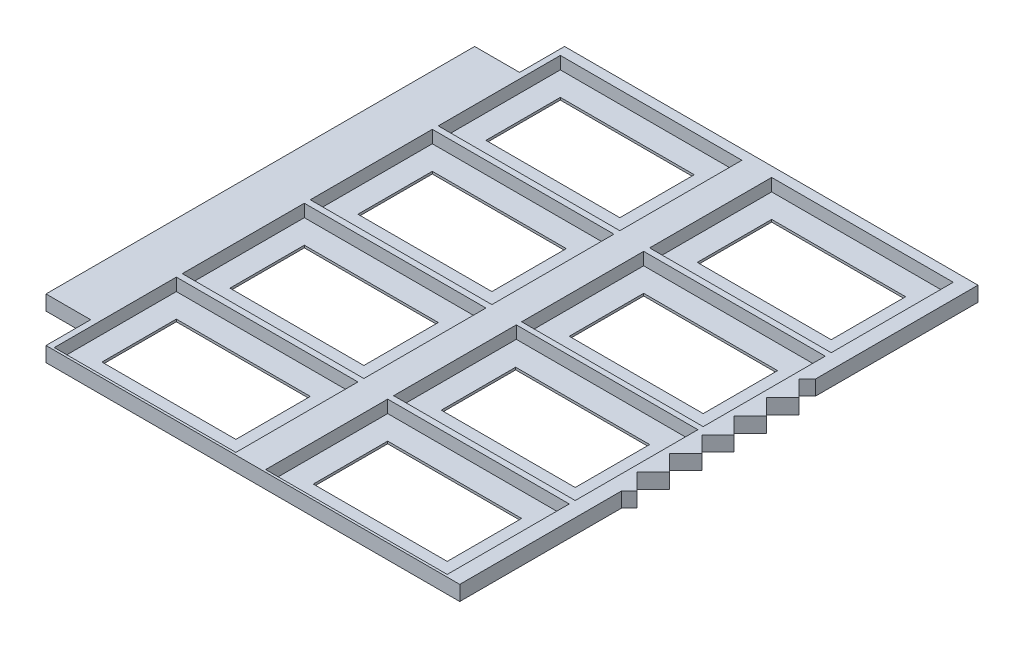
SolidWorks part; units mm, degrees
ref_plane "Front Plane" through (0, 0, 0) normal (0, 0, 1) x (1, 0, 0)
ref_plane "Top Plane" through (0, 0, 0) normal (0, 1, 0) x (1, 0, 0)
ref_plane "Right Plane" through (0, 0, 0) normal (1, 0, 0) x (0, 0, -1)
sketch "Sketch1" plane through (0, 0, 0) normal (0, 1, 0) x (1, 0, 0)
  line L0 (139.065, 94.1103) -> (139.065, -88.9) construction
  line L1 (-148.59, -107.95) -> (148.59, -107.95)
  line L2 (148.59, -107.95) -> (123.19, -107.95)
  line L3 (-156.21, 113.1603) -> (-137.0297, 113.1603)
  line L4 (148.59, -107.95) -> (148.59, 107.95)
  line L7 (148.59, -107.95) -> (-156.21, -107.95)
  line L8 (148.59, -107.95) -> (148.59, 113.1603)
  line L9 (148.59, 113.1603) -> (-156.21, 113.1603)
  line L10 (-156.21, -107.95) -> (-156.21, 113.1603)
  line L11 (-156.21, -107.95) -> (148.59, -107.95)
  line L12 (-156.21, -107.95) -> (-156.21, -106.95)
  line L13 (-156.21, -106.95) -> (148.59, -106.95)
  line L14 (148.59, -107.95) -> (148.59, -106.95)
  line L15 (148.59, -107.95) -> (148.59, 113.1603)
  line L16 (148.59, 113.1603) -> (123.19, 113.1603)
  line L17 (123.19, -107.95) -> (123.19, 113.1603)
  line L18 (123.19, -106.95) -> (45.72, -106.95)
  line L19 (123.19, -106.95) -> (123.19, -54.88)
  line L20 (123.19, -54.88) -> (45.72, -54.88)
  line L21 (45.72, -106.95) -> (45.72, -54.88)
  line L22 (123.19, -52.34) -> (45.72, -52.34)
  line L23 (123.19, -52.34) -> (123.19, -0.27)
  line L24 (123.19, -0.27) -> (45.72, -0.27)
  line L25 (45.72, -52.34) -> (45.72, -0.27)
  line L26 (123.19, 2.27) -> (45.72, 2.27)
  line L27 (123.19, 2.27) -> (123.19, 54.34)
  line L28 (123.19, 54.34) -> (45.72, 54.34)
  line L29 (45.72, 2.27) -> (45.72, 54.34)
  line L30 (123.19, 56.88) -> (45.72, 56.88)
  line L31 (123.19, 56.88) -> (123.19, 108.95)
  line L32 (123.19, 108.95) -> (45.72, 108.95)
  line L33 (45.72, 56.88) -> (45.72, 108.95)
  line L34 (33.02, -52.34) -> (-44.45, -52.34)
  line L35 (33.02, -106.95) -> (-44.45, -106.95)
  line L36 (33.02, -106.95) -> (33.02, -54.88)
  line L37 (33.02, -54.88) -> (-44.45, -54.88)
  line L38 (-44.45, -106.95) -> (-44.45, -54.88)
  line L39 (-57.15, -106.95) -> (-134.62, -106.95)
  line L40 (-57.15, -106.95) -> (-57.15, -54.88)
  line L41 (-57.15, -54.88) -> (-134.62, -54.88)
  line L42 (-134.62, -106.95) -> (-134.62, -54.88)
  line L43 (33.02, -52.34) -> (33.02, 0)
  line L44 (33.02, 0) -> (-44.45, 0)
  line L45 (-44.45, -52.34) -> (-44.45, 0)
  line L46 (-57.15, -52.34) -> (-134.62, -52.34)
  line L47 (-57.15, -52.34) -> (-57.15, -0.27)
  line L48 (-57.15, -0.27) -> (-134.62, -0.27)
  line L49 (-134.62, -52.34) -> (-134.62, -0.27)
  line L50 (33.02, 2.27) -> (-44.45, 2.27)
  line L51 (33.02, 2.27) -> (33.02, 54.34)
  line L52 (33.02, 54.34) -> (-44.45, 54.34)
  line L53 (-44.45, 2.27) -> (-44.45, 54.34)
  line L54 (-57.15, 2.27) -> (-134.62, 2.27)
  line L55 (-57.15, 2.27) -> (-57.15, 54.34)
  line L56 (-57.15, 54.34) -> (-134.62, 54.34)
  line L57 (-134.62, 2.27) -> (-134.62, 54.34)
  line L58 (33.02, 56.88) -> (-44.45, 56.88)
  line L59 (33.02, 56.88) -> (33.02, 108.95)
  line L60 (33.02, 108.95) -> (-44.45, 108.95)
  line L61 (-44.45, 56.88) -> (-44.45, 108.95)
  line L62 (-57.15, 56.88) -> (-134.62, 56.88)
  line L63 (-57.15, 56.88) -> (-57.15, 108.95)
  line L64 (-57.15, 108.95) -> (-134.62, 108.95)
  line L65 (-134.62, 56.88) -> (-134.62, 108.95)
  line L66 (-156.21, 113.1603) -> (-156.21, 100.4603)
  line L67 (-156.21, 113.1603) -> (-156.21, 93.98)
  line L68 (-156.21, 93.98) -> (-137.0297, 93.98)
  line L69 (-156.21, -107.95) -> (-137.16, -107.95)
  line L70 (-156.21, -107.95) -> (-156.21, -88.9)
  line L71 (-156.21, -88.9) -> (-137.16, -88.9)
  line L72 (-137.16, -107.95) -> (-137.16, -88.9)
  line L73 (-137.0297, 113.1603) -> (-137.0297, 93.98)
  line L74 (148.59, 113.1603) -> (129.54, 113.1603)
  line L75 (148.59, 113.1603) -> (148.59, 94.1103)
  line L76 (148.59, 94.1103) -> (129.54, 94.1103)
  line L77 (129.54, 113.1603) -> (129.54, 94.1103)
  line L78 (148.59, -107.95) -> (129.54, -107.95)
  line L79 (148.59, -107.95) -> (148.59, -88.9)
  line L80 (148.59, -88.9) -> (129.54, -88.9)
  line L81 (129.54, -107.95) -> (129.54, -88.9)
  circle A0 centre (139.065, 86.619) radius 1.5875
  circle A1 centre (139.065, 80.9106) radius 1.5875
  circle A2 centre (139.065, 75.3349) radius 1.5875
  point P0 (0, 0)
  point P3 (-137.16, -106.95)
  point P15 (123.19, -106.95)
  point P78 (-137.16, -107.95)
  point P79 (-156.21, -106.95)
  dimension "D1" = 215.9
  dimension "D2" = 297.18
  dimension "D3" = 1
  dimension "D4" = 25.4
  dimension "D5" = 2.54
  dimension "D6" = 2.54
  dimension "D7" = 2.54
  dimension "D8" = 12.7
  dimension "D9" = 12.7
extrude "Boss-Extrude3" add sketch "Sketch1" along normal blind 6.35 contours L76 L0 A0 A1 A2 L80 L15 | L0 L76 L77 L16 L17 L13 L81 L80 A2 A1 A0 | L9 L73 L68 L10 L71 L72 L13 L42 L41 L40 L38 L37 L36 L21 L20 L17 L22 L25 L24 L26 L29 L28 L30 L33 L32 L62 L65 L64 L63 L54 L57 L56 L55 L46 L49 L48 L47 L34 L45 L44 L43
sketch "Sketch2" plane through (0, 6.35, 0) normal (0, 1, 0) x (1, 0, 0)
  line L0 (148.59, -107.95) -> (148.59, -106.95) construction
  line L1 (129.54, -106.95) -> (148.59, -106.95)
  line L2 (129.54, -106.95) -> (129.54, -107.95)
  line L3 (129.54, -107.95) -> (148.59, -107.95)
  line L4 (148.59, -106.95) -> (148.59, -107.95)
  line L5 (-156.21, -107.95) -> (148.59, -107.95) construction
extrude "Cut-Extrude1" cut sketch "Sketch2" against normal through all
ref_plane "Plane1" through (-137.16, 6.35, 106.95) normal (0, -1, 0) x (-1, 0, 0)
sketch "Sketch4" plane through (0, 6.35, 0) normal (0, 1, 0) x (1, 0, 0)
  line L1 (-156.21, -107.95) -> (-137.16, -107.95)
  line L2 (-156.21, -107.95) -> (-156.21, -106.95)
  line L3 (-156.21, -106.95) -> (-137.16, -106.95)
  line L4 (-137.16, -107.95) -> (-137.16, -106.95)
extrude "Cut-Extrude2" cut sketch "Sketch4" against normal through all
sketch "Sketch5" plane through (0, 0, -108.95) normal (0, 0, 1) x (1, 0, 0)
  line L1 (-134.62, 6.35) -> (-134.62, 0) construction
  line L2 (123.19, 0) -> (-134.62, 0)
  line L3 (123.19, 0) -> (123.19, 1)
  line L4 (123.19, 1) -> (-134.62, 1)
  line L5 (-134.62, 0) -> (-134.62, 1)
extrude "Boss-Extrude4" add sketch "Sketch5" along normal through all
sketch "Sketch6" plane through (0, 1, 0) normal (0, 1, 0) x (1, 0, 0)
  line L0 (-134.62, 2.27) -> (-57.15, 54.34) construction
  line L1 (-134.62, 108.95) -> (-57.15, 56.88) construction
  line L2 (-57.15, 108.95) -> (-134.62, 56.88) construction
  line L3 (-124.46, 67.04) -> (-67.31, 67.04)
  line L4 (-124.46, 67.04) -> (-124.46, 98.79)
  line L5 (-124.46, 98.79) -> (-67.31, 98.79)
  line L6 (-67.31, 67.04) -> (-67.31, 98.79)
  line L7 (-124.46, 67.04) -> (-67.31, 98.79) construction
  line L8 (-124.46, 98.79) -> (-67.31, 67.04) construction
  line L9 (-134.62, 2.27) -> (-57.15, 2.27) construction
  line L10 (-134.62, 54.34) -> (-57.15, 54.34) construction
  line L11 (-57.15, 54.34) -> (-57.15, 2.27) construction
  line L12 (-134.62, 54.34) -> (-57.15, 2.27) construction
  line L13 (-57.15, -0.27) -> (-134.62, -52.34) construction
  line L14 (-124.46, 44.18) -> (-67.31, 44.18)
  line L15 (-124.46, 44.18) -> (-124.46, 12.43)
  line L16 (-124.46, 12.43) -> (-67.31, 12.43)
  line L17 (-67.31, 44.18) -> (-67.31, 12.43)
  line L18 (-124.46, 44.18) -> (-67.31, 12.43) construction
  line L19 (-124.46, 12.43) -> (-67.31, 44.18) construction
  line L20 (-134.62, -0.27) -> (-57.15, -52.34) construction
  line L21 (-57.15, -0.27) -> (-57.15, -52.34) construction
  line L22 (-57.15, -54.88) -> (-134.62, -106.95) construction
  line L23 (-124.46, -10.43) -> (-67.31, -10.43)
  line L24 (-124.46, -10.43) -> (-124.46, -42.18)
  line L25 (-124.46, -42.18) -> (-67.31, -42.18)
  line L26 (-67.31, -10.43) -> (-67.31, -42.18)
  line L27 (-124.46, -10.43) -> (-67.31, -42.18) construction
  line L28 (-124.46, -42.18) -> (-67.31, -10.43) construction
  line L29 (-134.62, -54.88) -> (-57.15, -54.88) construction
  line L30 (-134.62, -54.88) -> (-57.15, -106.95) construction
  line L31 (33.02, 108.95) -> (-44.45, 56.88) construction
  line L32 (-124.46, -65.04) -> (-67.31, -65.04)
  line L33 (-124.46, -65.04) -> (-124.46, -96.79)
  line L34 (-124.46, -96.79) -> (-67.31, -96.79)
  line L35 (-67.31, -65.04) -> (-67.31, -96.79)
  line L36 (-124.46, -65.04) -> (-67.31, -96.79) construction
  line L37 (-124.46, -96.79) -> (-67.31, -65.04) construction
  line L38 (33.02, 108.95) -> (33.02, 56.88) construction
  line L39 (33.02, 108.95) -> (-44.45, 108.95) construction
  line L40 (33.02, 56.88) -> (-44.45, 108.95) construction
  line L41 (-44.45, 56.88) -> (33.02, 56.88) construction
  line L42 (123.19, 108.95) -> (45.72, 56.88) construction
  line L43 (-34.29, 67.04) -> (22.86, 67.04)
  line L44 (-34.29, 67.04) -> (-34.29, 98.79)
  line L45 (-34.29, 98.79) -> (22.86, 98.79)
  line L46 (22.86, 67.04) -> (22.86, 98.79)
  line L47 (-34.29, 67.04) -> (22.86, 98.79) construction
  line L48 (-34.29, 98.79) -> (22.86, 67.04) construction
  line L49 (45.72, 108.95) -> (123.19, 56.88) construction
  line L51 (55.88, 98.79) -> (113.03, 98.79)
  line L52 (55.88, 98.79) -> (55.88, 67.04)
  line L53 (55.88, 67.04) -> (113.03, 67.04)
  line L54 (113.03, 98.79) -> (113.03, 67.04)
  line L55 (55.88, 98.79) -> (113.03, 67.04) construction
  line L56 (55.88, 67.04) -> (113.03, 98.79) construction
  line L57 (-34.29, 12.43) -> (22.86, 12.43)
  line L58 (-34.29, 12.43) -> (-34.29, 44.18)
  line L59 (-34.29, 44.18) -> (22.86, 44.18)
  line L60 (22.86, 12.43) -> (22.86, 44.18)
  line L61 (-34.29, 12.43) -> (22.86, 44.18) construction
  line L62 (-34.29, 44.18) -> (22.86, 12.43) construction
  line L63 (-34.29, -42.18) -> (22.86, -42.18)
  line L64 (-34.29, -42.18) -> (-34.29, -10.43)
  line L65 (-34.29, -10.43) -> (22.86, -10.43)
  line L66 (22.86, -42.18) -> (22.86, -10.43)
  line L67 (-34.29, -42.18) -> (22.86, -10.43) construction
  line L68 (-34.29, -10.43) -> (22.86, -42.18) construction
  line L69 (-34.29, -96.79) -> (22.86, -96.79)
  line L70 (-34.29, -96.79) -> (-34.29, -65.04)
  line L71 (-34.29, -65.04) -> (22.86, -65.04)
  line L72 (22.86, -96.79) -> (22.86, -65.04)
  line L73 (-34.29, -96.79) -> (22.86, -65.04) construction
  line L74 (-34.29, -65.04) -> (22.86, -96.79) construction
  line L75 (55.88, -96.79) -> (113.03, -96.79)
  line L76 (55.88, -96.79) -> (55.88, -65.04)
  line L77 (55.88, -65.04) -> (113.03, -65.04)
  line L78 (113.03, -96.79) -> (113.03, -65.04)
  line L79 (55.88, -96.79) -> (113.03, -65.04) construction
  line L80 (55.88, -65.04) -> (113.03, -96.79) construction
  line L81 (55.88, -42.18) -> (113.03, -42.18)
  line L82 (55.88, -42.18) -> (55.88, -10.43)
  line L83 (55.88, -10.43) -> (113.03, -10.43)
  line L84 (113.03, -42.18) -> (113.03, -10.43)
  line L85 (55.88, -42.18) -> (113.03, -10.43) construction
  line L86 (55.88, -10.43) -> (113.03, -42.18) construction
  line L87 (55.88, 12.43) -> (113.03, 12.43)
  line L88 (55.88, 12.43) -> (55.88, 44.18)
  line L89 (55.88, 44.18) -> (113.03, 44.18)
  line L90 (113.03, 12.43) -> (113.03, 44.18)
  line L91 (55.88, 12.43) -> (113.03, 44.18) construction
  line L92 (55.88, 44.18) -> (113.03, 12.43) construction
  point P4 (-95.885, 82.915)
  point P23 (-95.885, 28.305)
  point P37 (-95.885, -26.305)
  point P51 (-95.885, -80.915)
  point P68 (-5.715, 82.915)
  point P81 (84.455, 82.915)
  point P86 (-5.715, 28.305)
  point P91 (-5.715, -26.305)
  point P96 (-5.715, -80.915)
  point P101 (84.455, -80.915)
  point P106 (84.455, -26.305)
  point P111 (84.455, 28.305)
extrude "Cut-Extrude3" cut sketch "Sketch6" against normal through all
sketch "Sketch7" plane through (0, 6.35, 0) normal (0, 1, 0) x (1, 0, 0)
  line L0 (39.37, 43.8468) -> (35.7888, 40.2655)
  line L3 (39.37, 43.8468) -> (39.37, 113.1603)
  line L6 (35.7888, 40.2655) -> (42.6794, 33.3749)
  line L7 (42.6794, 33.3749) -> (35.7888, 26.4843)
  line L8 (35.7888, 26.4843) -> (42.6794, 19.5937)
  line L9 (42.6794, 19.5937) -> (39.37, 16.2843)
  line L10 (129.54, 113.1603) -> (-137.0297, 113.1603) construction
  line L11 (39.37, -38.8407) -> (39.37, -107.95)
  line L13 (39.37, 16.2843) -> (35.7888, 12.7031)
  line L14 (35.7888, 12.7031) -> (42.6794, 5.8124)
  line L15 (42.6794, 5.8124) -> (35.7888, -1.0782)
  line L16 (35.7888, -1.0782) -> (42.6794, -7.9688)
  line L17 (42.6794, -7.9688) -> (35.7888, -14.8594)
  line L18 (35.7888, -14.8594) -> (39.37, -18.4406)
  line L19 (39.37, -18.4406) -> (42.6794, -21.75)
  line L20 (42.6794, -21.75) -> (35.7888, -28.6407)
  line L21 (35.7888, -28.6407) -> (42.6794, -35.5313)
  line L22 (42.6794, -35.5313) -> (39.37, -38.8407)
  line L23 (-137.16, -107.95) -> (129.54, -107.95) construction
  line L25 (39.37, -107.95) -> (150.0272, -107.95)
  line L27 (39.37, 113.1603) -> (150.0272, 113.1603)
  line L28 (150.0272, -107.95) -> (150.0272, 113.1603)
extrude "Cut-Extrude4" cut sketch "Sketch7" against normal through all
